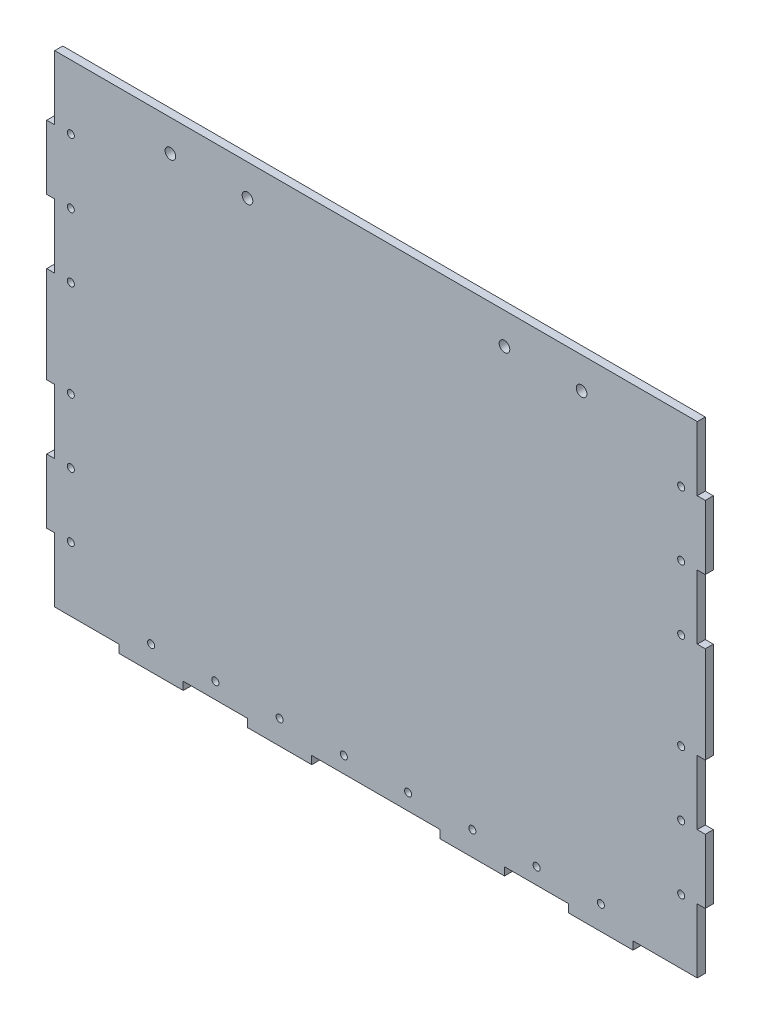
SolidWorks part; units mm, degrees
ref_plane "前视基准面" through (0, 0, 0) normal (0, 0, 1) x (1, 0, 0)
ref_plane "上视基准面" through (0, 0, 0) normal (0, 1, 0) x (1, 0, 0)
ref_plane "右视基准面" through (0, 0, 0) normal (1, 0, 0) x (0, 0, -1)
sketch "草图1" plane through (0, 0, 0) normal (0, 0, 1) x (1, 0, 0)
  line L2 (-200, 150) -> (200, 150)
  line L3 (200, -150) -> (200, -110)
  line L4 (-200, -150) -> (-200, -110)
  line L5 (-200, -150) -> (-160, -150)
  line L6 (-200, -150) -> (-160, -150)
  line L7 (-160, -150) -> (-160, -155)
  line L8 (-160, -155) -> (-120, -155)
  line L9 (-120, -155) -> (-120, -150)
  line L10 (-120, -150) -> (-80, -150)
  line L11 (-80, -150) -> (-80, -155)
  line L12 (-80, -155) -> (-40, -155)
  line L13 (-40, -155) -> (-40, -150)
  line L14 (-40, -150) -> (40, -150)
  line L15 (40, -150) -> (40, -155)
  line L16 (40, -155) -> (80, -155)
  line L17 (80, -155) -> (80, -150)
  line L18 (80, -150) -> (120, -150)
  line L19 (120, -150) -> (120, -155)
  line L20 (120, -155) -> (160, -155)
  line L21 (160, -155) -> (160, -150)
  line L22 (80, -150) -> (120, -150)
  line L23 (-120, -150) -> (-80, -150)
  line L24 (-40, -150) -> (40, -150)
  line L25 (160, -150) -> (200, -150)
  line L26 (-200, 110) -> (-200, 150)
  line L27 (-200, -70) -> (-200, -30)
  line L28 (-205, -30) -> (-205, 30)
  line L29 (-205, 30) -> (-200, 30)
  line L30 (-200, 30) -> (-200, 70)
  line L31 (-200, 70) -> (-205, 70)
  line L32 (-205, 70) -> (-205, 110)
  line L33 (-205, 110) -> (-200, 110)
  line L34 (-205, -30) -> (-200, -30)
  line L35 (-200, -70) -> (-205, -70)
  line L36 (-205, -70) -> (-205, -110)
  line L37 (-205, -110) -> (-200, -110)
  line L38 (-200, 30) -> (-200, 70)
  line L39 (200, 110) -> (200, 150)
  line L40 (205, -70) -> (205, -110)
  line L41 (205, -110) -> (200, -110)
  line L42 (200, -70) -> (205, -70)
  line L43 (205, -30) -> (200, -30)
  line L44 (205, -30) -> (205, 30)
  line L45 (205, 30) -> (200, 30)
  line L46 (200, 70) -> (205, 70)
  line L47 (205, 70) -> (205, 110)
  line L48 (205, 110) -> (200, 110)
  line L49 (200, 30) -> (200, 70)
  line L50 (200, -70) -> (200, -30)
  circle A0 centre (-140, -140) radius 2.2
  circle A1 centre (-100, -140) radius 2.2
  circle A2 centre (-60, -140) radius 2.2
  circle A3 centre (-20, -140) radius 2.2
  circle A4 centre (20, -140) radius 2.2
  circle A5 centre (60, -140) radius 2.2
  circle A6 centre (100, -140) radius 2.2
  circle A7 centre (140, -140) radius 2.2
  circle A8 centre (-190, 110) radius 2.2
  circle A9 centre (-190, 70) radius 2.2
  circle A10 centre (-190, 30) radius 2.2
  circle A11 centre (-190, -30) radius 2.2
  circle A12 centre (-190, -70) radius 2.2
  circle A13 centre (-190, -110) radius 2.2
  circle A14 centre (190, -110) radius 2.2
  circle A15 centre (190, -70) radius 2.2
  circle A16 centre (190, -30) radius 2.2
  circle A17 centre (190, 30) radius 2.2
  circle A18 centre (190, 70) radius 2.2
  circle A19 centre (190, 110) radius 2.2
extrude "凸台-拉伸1" add sketch "草图1" along normal blind 5 contours L42 L50 L43 L44 L45 L49 L46 L47 L48 L39 L2 L26 L33 L32 L31 L30 L29 L28 L34 L27 L35 L36 L37 L4 L5 L7 L8 L9 L10 L11 L12 L13 L14 L15 L16 L17 L18 L19 L20 L21 L25 L3 L41 L40 A18 A16 A14
sketch "草图2" plane through (0, 0, 5) normal (0, 0, 1) x (1, 0, 0)
  circle A0 centre (-80, 130.5) radius 3.3
  circle A1 centre (-128, 130.5) radius 3.3
  circle A2 centre (128, 130.5) radius 3.3
  circle A3 centre (80, 130.5) radius 3.3
extrude "切除-拉伸1" cut sketch "草图2" against normal blind 10
